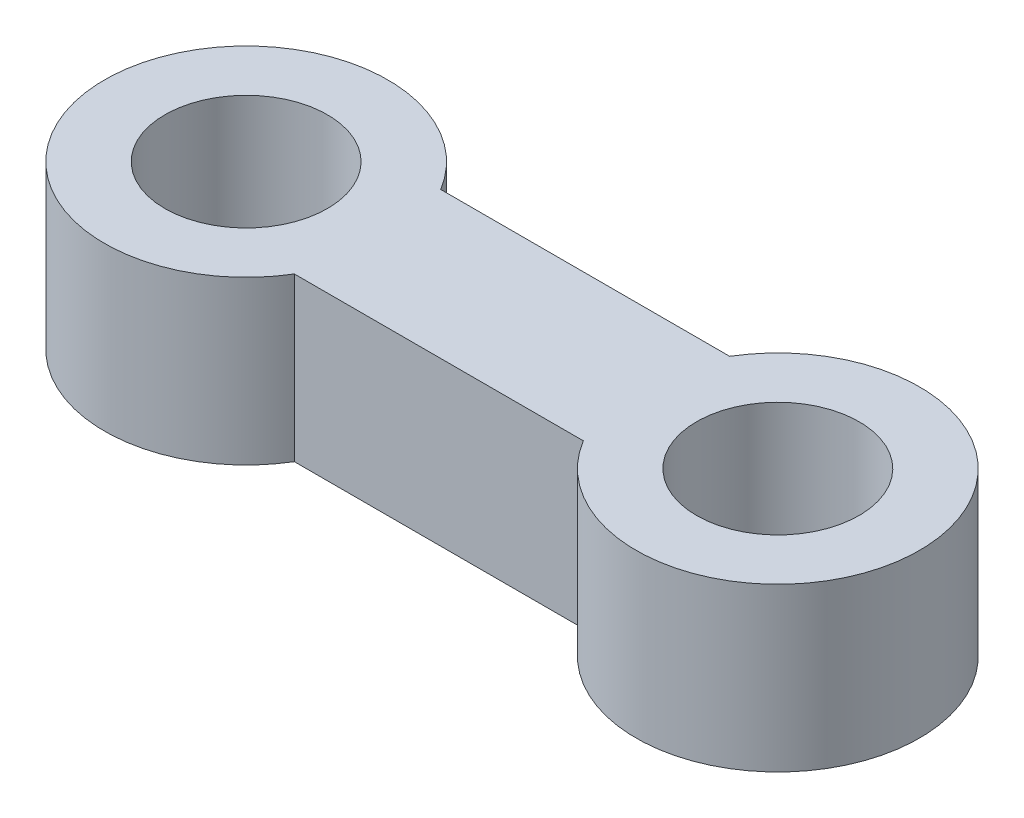
SolidWorks part; units mm, degrees
ref_plane "Front Plane" through (0, 0, 0) normal (0, 0, 1) x (1, 0, 0)
ref_plane "Top Plane" through (0, 0, 0) normal (0, 1, 0) x (1, 0, 0)
ref_plane "Right Plane" through (0, 0, 0) normal (1, 0, 0) x (0, 0, -1)
sketch "Sketch1" plane through (0, 0, 0) normal (0, 1, 0) x (1, 0, 0)
  line L0 (-4.905, 0) -> (4.905, 0) construction
  line L1 (-4.905, 2.6145) -> (4.905, 2.6145)
  line L2 (-4.905, -2.6145) -> (4.905, -2.6145)
  arc A0 (-4.905, 2.6145) -> (-4.905, -2.6145) centre (-4.905, 0) ccw
  arc A1 (4.905, -2.6145) -> (4.905, 2.6145) centre (4.905, 0) ccw
  point P3 (0, 0)
  point P8 (0, 0)
  dimension "D1" = 9.81
extrude "Boss-Extrude1" add sketch "Sketch1" along normal blind 3
sketch "Sketch2" plane through (0, 3, 0) normal (0, 1, 0) x (1, 0, 0)
  line L0 (-4.905, 0) -> (0, 0) construction
  line L1 (0, 0) -> (4.905, 0) construction
  circle A0 centre (-4.905, 0) radius 1.5
  circle A1 centre (4.905, 0) radius 1.5
  dimension "D1" = 3
  dimension "D2" = 4.905
extrude "Cut-Extrude1" cut sketch "Sketch2" against normal through all
sketch "Sketch3" plane through (0, 3, 0) normal (0, 1, 0) x (1, 0, 0)
  line L0 (-2.666, 1.35) -> (2.666, 1.35)
  line L1 (-2.666, -1.35) -> (2.666, -1.35)
  line L2 (4.905, 2.6145) -> (-4.905, 2.6145) construction
  line L3 (-4.905, -2.6145) -> (4.905, -2.6145) construction
  line L4 (-2.666, 1.35) -> (-2.666, -1.35) construction
  line L5 (2.666, 1.35) -> (2.666, -1.35) construction
  line L6 (-4.905, -2.6145) -> (4.905, -2.6145)
  line L7 (-4.905, 2.6145) -> (4.905, 2.6145)
  line L8 (-4.905, 0) -> (-2.666, 0) construction
  line L9 (2.666, 0) -> (4.905, 0) construction
  line L10 (-4.905, 2.6145) -> (-4.905, -2.6145) construction
  line L11 (4.905, 2.6145) -> (4.905, -2.6145) construction
  arc A0 (-2.666, 1.35) -> (-4.905, 2.6145) centre (-4.905, 0) ccw
  arc A1 (-2.666, -1.35) -> (-4.905, -2.6145) centre (-4.905, 0) cw
  arc A2 (2.666, 1.35) -> (4.905, 2.6145) centre (4.905, 0) cw
  arc A3 (2.666, -1.35) -> (4.905, -2.6145) centre (4.905, 0) ccw
  dimension "D1" = 2.7
extrude "Cut-Extrude2" cut sketch "Sketch3" against normal through all
